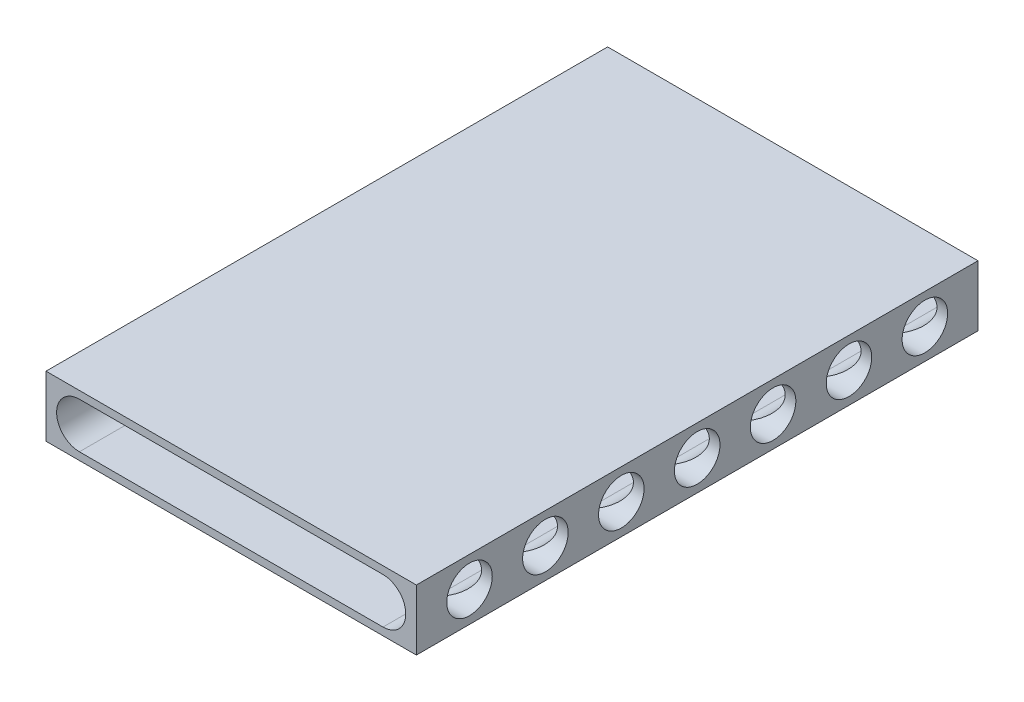
SolidWorks part; units mm, degrees
ref_plane "Front Plane" through (0, 0, 0) normal (0, 0, 1) x (1, 0, 0)
ref_plane "Top Plane" through (0, 0, 0) normal (0, 1, 0) x (1, 0, 0)
ref_plane "Right Plane" through (0, 0, 0) normal (1, 0, 0) x (0, 0, -1)
sketch "Sketch1" plane through (0, 0, 0) normal (0, 1, 0) x (1, 0, 0)
  line L1 (-61, -92.5) -> (61, -92.5)
  line L2 (-61, -92.5) -> (-61, 92.5)
  line L3 (-61, 92.5) -> (61, 92.5)
  line L4 (61, -92.5) -> (61, 92.5)
  line L5 (-61, -92.5) -> (61, 92.5) construction
  line L6 (-61, 92.5) -> (61, -92.5) construction
  point P0 (0, 0)
  dimension "D1" = 122
  dimension "D2" = 185
extrude "Boss-Extrude1" add sketch "Sketch1" along normal blind 20
sketch "Sketch2" plane through (61, 0, 0) normal (1, 0, 0) x (0, 0, -1)
  line L0 (-92.5, 20) -> (-92.5, 0) construction
  line L3 (-92.5, 10) -> (92.5, 10) construction
  line L4 (92.5, 20) -> (92.5, 0) construction
  circle A0 centre (-75, 10) radius 7.5
  circle A1 centre (-50, 10) radius 7.5
  circle A2 centre (-25, 10) radius 7.5
  circle A3 centre (0, 10) radius 7.5
  circle A4 centre (25, 10) radius 7.5
  circle A5 centre (50, 10) radius 7.5
  circle A6 centre (75, 10) radius 7.5
  point P4 (0, 0)
  dimension "D1" = 15
  dimension "D2" = 17.5
  dimension "D3" = 7
  dimension "D4" = 17.5
sketch "Sketch3" plane through (0, 0, 92.5) normal (0, 0, 1) x (1, 0, 0)
  line L0 (-50, 10) -> (50, 10) construction
  line L1 (-50, 17.5) -> (50, 17.5)
  line L2 (-50, 2.5) -> (50, 2.5)
  line L3 (0, 20) -> (0, 0) construction
  line L4 (-61, 20) -> (61, 20) construction
  arc A0 (-50, 17.5) -> (-50, 2.5) centre (-50, 10) ccw
  arc A1 (50, 2.5) -> (50, 17.5) centre (50, 10) ccw
  point P2 (0, 10)
  point P7 (0, 0)
  dimension "D1" = 15
  dimension "D2" = 100
extrude "Cut-Extrude1" cut sketch "Sketch3" against normal through all
extrude "Cut-Extrude2" cut sketch "Sketch2" against normal up to next
